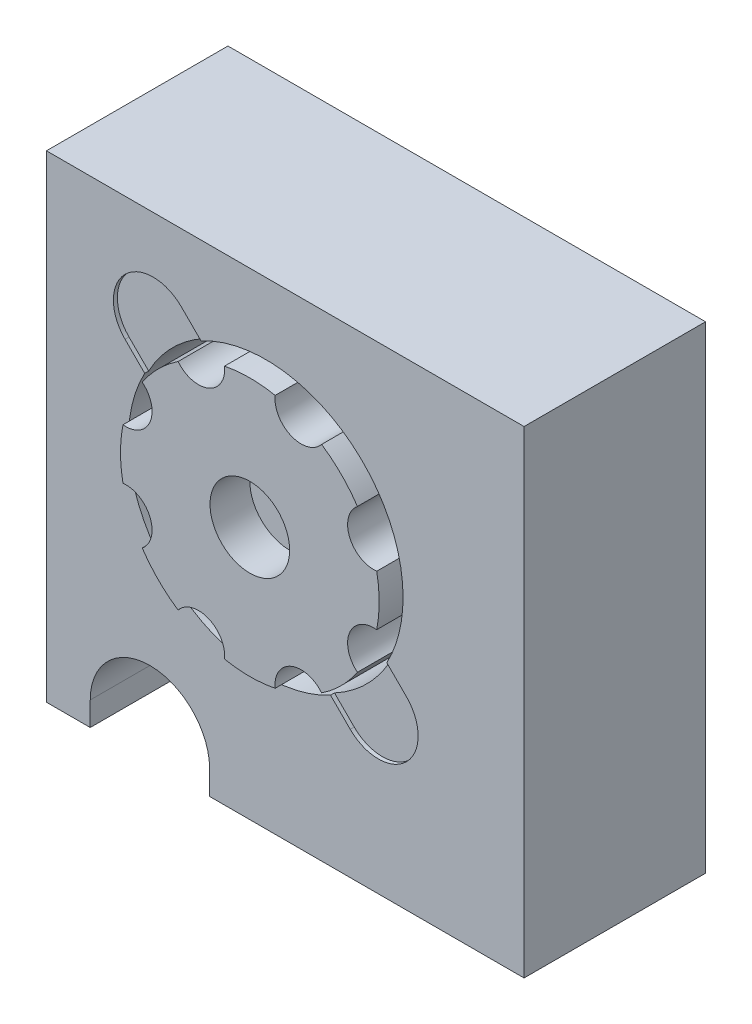
SolidWorks part; units mm, degrees
ref_plane "Plan de face" through (0, 0, 0) normal (0, 0, 1) x (1, 0, 0)
ref_plane "Plan de dessus" through (0, 0, 0) normal (0, 1, 0) x (1, 0, 0)
ref_plane "Plan de droite" through (0, 0, 0) normal (1, 0, 0) x (0, 0, -1)
sketch "Sketch1" plane through (0, 0, 0) normal (0, 0, 1) x (1, 0, 0)
  line L1 (-3, -3) -> (3, -3)
  line L2 (-3, -3) -> (-3, 3)
  line L3 (-3, 3) -> (3, 3)
  line L4 (3, -3) -> (3, 3)
  line L5 (-3, -3) -> (3, 3) construction
  line L6 (-3, 3) -> (3, -3) construction
  point P0 (0, 0)
  dimension "D1" = 6
extrude "Boss-Extrude1" add sketch "Sketch1" along normal blind 2.28
sketch "Sketch2" plane through (0, 0, 2.28) normal (0, 0, 1) x (1, 0, 0)
  line L0 (3, 3) -> (-3, 3) construction
  line L1 (-3, 3) -> (-3, -3) construction
  circle A0 centre (-0.245, 0.382) radius 1.725
  dimension "D1" = 2.618
  dimension "D3" = 3.45
  dimension "D2" = 2.755
extrude "Cut-Extrude1" cut sketch "Sketch2" against normal blind 1
sketch "Sketch3" plane through (0, 0, 2.28) normal (0, 0, 1) x (1, 0, 0)
  line L0 (0.8157, -1.3858) -> (-2.0128, 1.4427)
  line L3 (1.5228, -0.6787) -> (-1.3057, 2.1498)
  line L4 (0.8157, -1.3858) -> (-1.3057, 2.1498) construction
  line L5 (-2.0128, 1.4427) -> (1.5228, -0.6787) construction
  line L6 (3, 3) -> (-3, 3) construction
  circle A0 centre (-0.245, 0.382) radius 1.725 construction
  arc A2 (0.8157, -1.3858) -> (1.5228, -0.6787) centre (1.1692, -1.0322) ccw
  arc A3 (-2.0128, 1.4427) -> (-1.3057, 2.1498) centre (-1.6592, 1.7962) cw
  point P1 (-0.245, 0.382)
  point P6 (0, 0)
  dimension "D3" = 4
  dimension "D1" = 1
  dimension "D2" = 45
extrude "Cut-Extrude2" cut sketch "Sketch3" against normal blind 0.05
sketch "Sketch4" plane through (0, 0, 2.28) normal (0, 0, 1) x (1, 0, 0)
  line L0 (-2.45, -2.7) -> (-2.45, -3)
  line L1 (-3, -3) -> (3, -3) construction
  line L2 (-2.45, -3) -> (-0.95, -3)
  line L3 (-0.95, -3) -> (-0.95, -2.7)
  line L4 (-3, 3) -> (-3, -3) construction
  arc A0 (-0.95, -2.7) -> (-2.45, -2.7) centre (-1.7, -2.7) ccw
  point P8 (-1.8442, -2.0466)
  dimension "D1" = 0.75
  dimension "D2" = 0.3
  dimension "D3" = 1.3
extrude "Cut-Extrude3" cut sketch "Sketch4" against normal blind 1
sketch "Sketch5" plane through (0, 0, 1.28) normal (0, 0, 1) x (1, 0, 0)
  circle A0 centre (-0.245, 0.382) radius 1.625
  arc A1 (1.2759, -0.4318) -> (-1.0588, 1.9029) centre (-0.245, 0.382) ccw construction
  circle A2 centre (-0.245, 0.382) radius 1.725 construction
  dimension "D1" = 0.1
extrude "Boss-Extrude2" add sketch "Sketch5" along normal blind 1.2
sketch "Sketch6" plane through (0, 0, 2.48) normal (0, 0, 1) x (1, 0, 0)
  arc A0 (-1.8976, 0.0517) -> (-1.6471, -0.553) centre (-0.245, 0.382) ccw
  circle A1 centre (-0.245, 0.382) radius 1.625 construction
  arc A4 (0.0853, 2.0346) -> (0.69, 1.7841) centre (0.3999, 1.939) ccw
  arc A6 (1.1571, 1.317) -> (1.4076, 0.7123) centre (1.312, 1.0269) ccw
  arc A8 (1.4076, 0.0517) -> (1.1571, -0.553) centre (1.312, -0.2629) ccw
  arc A10 (0.69, -1.0201) -> (0.0853, -1.2706) centre (0.3999, -1.175) ccw
  arc A12 (-0.5753, -1.2706) -> (-1.18, -1.0201) centre (-0.8899, -1.175) ccw
  arc A14 (-1.6471, -0.553) -> (-1.8976, 0.0517) centre (-1.802, -0.2629) ccw
  arc A16 (-1.8976, 0.7123) -> (-1.6471, 1.317) centre (-1.802, 1.0269) ccw
  arc A18 (-1.18, 1.7841) -> (-0.5753, 2.0346) centre (-0.8899, 1.939) ccw
  arc A21 (1.4076, 0.7123) -> (1.1571, 1.317) centre (-0.245, 0.382) ccw
  arc A23 (1.1571, -0.553) -> (1.4076, 0.0517) centre (-0.245, 0.382) ccw
  arc A25 (0.0853, -1.2706) -> (0.69, -1.0201) centre (-0.245, 0.382) ccw
  arc A27 (-1.18, -1.0201) -> (-0.5753, -1.2706) centre (-0.245, 0.382) ccw
  arc A29 (-1.6471, 1.317) -> (-1.8976, 0.7123) centre (-0.245, 0.382) ccw
  arc A31 (-0.5753, 2.0346) -> (-1.18, 1.7841) centre (-0.245, 0.382) ccw
  arc A33 (0.69, 1.7841) -> (0.0853, 2.0346) centre (-0.245, 0.382) ccw
  point P54 (0, 0)
  point P68 (0, 0)
  point P69 (0.3999, 1.939)
extrude "Cut-Extrude6" cut sketch "Sketch6" against normal up to surface (1.2 mm away) up to face at (1.38, 0.382, 1.28)
sketch "Sketch7" plane through (0, 0, 2.48) normal (0, 0, 1) x (1, 0, 0)
  circle A0 centre (-0.245, 0.382) radius 0.5
  dimension "D1" = 1
extrude "Cut-Extrude7" cut sketch "Sketch7" against normal blind 0.5
